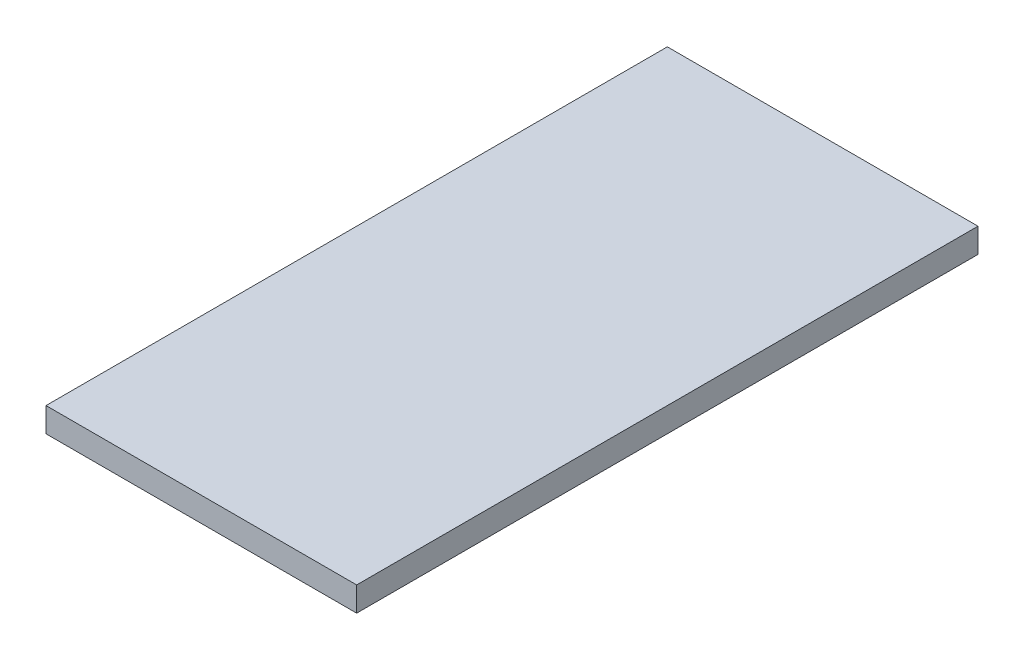
SolidWorks part; units mm, degrees
ref_plane "Front Plane" through (0, 0, 0) normal (0, 0, 1) x (1, 0, 0)
ref_plane "Top Plane" through (0, 0, 0) normal (0, 1, 0) x (1, 0, 0)
ref_plane "Right Plane" through (0, 0, 0) normal (1, 0, 0) x (0, 0, -1)
sketch "Sketch1" plane through (0, 0, 0) normal (0, 1, 0) x (1, 0, 0)
  line L1 (0, 0) -> (25.4, 0)
  line L2 (0, 0) -> (0, 50.8)
  line L3 (0, 50.8) -> (25.4, 50.8)
  line L4 (25.4, 0) -> (25.4, 50.8)
  dimension "D1" = 25.4
  dimension "D2" = 50.8
extrude "Boss-Extrude1" add sketch "Sketch1" along normal blind 2
